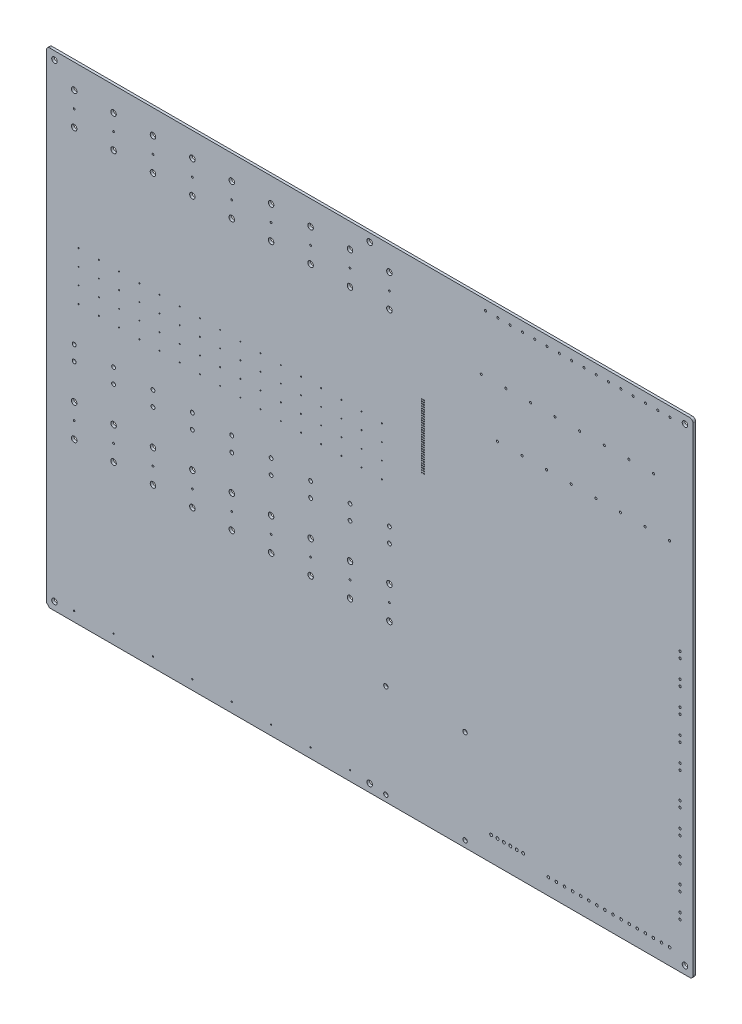
SolidWorks part; units mm, degrees
ref_plane "Front Plane" through (0, 0, 0) normal (0, 0, 1) x (1, 0, 0)
ref_plane "Top Plane" through (0, 0, 0) normal (0, 1, 0) x (1, 0, 0)
ref_plane "Right Plane" through (0, 0, 0) normal (1, 0, 0) x (0, 0, -1)
sketch "Sketch2" plane through (0, 0, 0) normal (0, 0, 1) x (1, 0, 0)
  line L1 (30, 30) -> (430, 30)
  line L2 (30, 30) -> (30, 330)
  line L3 (30, 330) -> (430, 330)
  line L4 (430, 30) -> (430, 330)
  dimension "D1" = 400
  dimension "D2" = 300
  dimension "D3" = 30
  dimension "D4" = 30
extrude "Boss-Extrude2" add sketch "Sketch2" along normal blind 1.6
fillet "Fillet1" radius 2 3 edges at (430, 30, 0.8) (430, 330, 0.8) (30, 330, 0.8)
chamfer "Chamfer1" distance 2 angle 45 1 edges at (30, 30, 0.8)
hole_wizard "6 x Ø3.4 Board Fixture " positions "Sketch3" profile "Sketch4" hole size "Ø3.4" standard "ISO"
sketch "Sketch3" plane through (0, 0, 1.6) normal (0, 0, 1) x (1, 0, 0)
  point P0 (35, 35)
  point P2 (230, 35)
  point P4 (425, 35)
  point P6 (425, 325)
  point P8 (230, 325)
  point P10 (35, 325)
  dimension "D1" = 35
  dimension "D2" = 230
  dimension "D3" = 425
  dimension "D4" = 35
  dimension "D5" = 325
sketch "Sketch4" plane through (35, 35, 1.6) normal (1, 0, 0) x (0, -1, 0)
  line L0 (0, 0) -> (0, 2.8215)
  line L1 (0, 2.8215) -> (1.7, 1.8)
  line L2 (1.7, 1.8) -> (1.7, 0)
  line L5 (1.7, 0) -> (0, 0)
  line L10 (0, 2.8215) -> (-1.7, 1.8) construction
  line L11 (0, -6.35) -> (0, 107.95) construction
  dimension "Hole Dia." = 3.4
  dimension "Hole Depth" = 1.8
  dimension "Drill Angle" = 118
sketch "Sketch9" plane through (0, 0, 1.6) normal (0, 0, 1) x (1, 0, 0)
  line L0 (47.188, 330) -> (47.188, 30) construction
  line L1 (428, 330) -> (32, 330) construction
  line L2 (32, 30) -> (428, 30) construction
  line L3 (71.563, 330) -> (71.563, 30) construction
  line L4 (95.938, 330) -> (95.938, 30) construction
  line L5 (120.313, 330) -> (120.313, 30) construction
  line L6 (144.688, 330) -> (144.688, 30) construction
  line L7 (169, 330) -> (169, 30) construction
  line L8 (193.446, 330) -> (193.446, 30) construction
  line L9 (217.812, 330) -> (217.812, 30) construction
  line L10 (242.188, 330) -> (242.188, 30) construction
  dimension "D1" = 47.188
  dimension "D2" = 71.563
  dimension "D3" = 95.938
  dimension "D4" = 120.313
  dimension "D5" = 144.688
  dimension "D6" = 169
  dimension "D7" = 193.446
  dimension "D8" = 217.812
  dimension "D9" = 242.188
hole_wizard "Ø3.4 (3.4) Diameter Hole3" positions "Sketch10" profile "Sketch11" hole size "Ø3.4" standard "ISO"
sketch "Sketch10" plane through (0, 0, 1.6) normal (0, 0, 1) x (1, 0, 0)
  line L0 (47.188, 330) -> (47.188, 30) construction
  line L1 (71.563, 330) -> (71.563, 30) construction
  line L2 (95.938, 330) -> (95.938, 30) construction
  line L3 (120.313, 330) -> (120.313, 30) construction
  line L4 (169, 330) -> (169, 30) construction
  line L5 (193.446, 330) -> (193.446, 30) construction
  line L6 (217.812, 330) -> (217.812, 30) construction
  line L7 (242.188, 330) -> (242.188, 30) construction
  line L8 (144.688, 330) -> (144.688, 30) construction
  point P0 (47.188, 314.956)
  point P2 (71.563, 314.956)
  point P4 (95.938, 314.956)
  point P6 (120.313, 314.956)
  point P8 (144.688, 314.956)
  point P10 (169, 314.956)
  point P12 (193.446, 314.956)
  point P14 (217.812, 314.956)
  point P16 (242.188, 314.956)
  point P18 (47.188, 294.956)
  point P20 (71.563, 294.956)
  point P22 (95.938, 294.956)
  point P24 (120.313, 294.956)
  point P26 (144.688, 294.956)
  point P28 (169, 294.956)
  point P30 (193.446, 294.956)
  point P32 (217.812, 294.956)
  point P34 (242.188, 294.956)
  point P36 (47.188, 147.956)
  point P38 (71.563, 147.956)
  point P40 (95.938, 147.956)
  point P42 (120.313, 147.956)
  point P44 (144.688, 147.956)
  point P46 (169, 147.956)
  point P48 (193.446, 147.956)
  point P50 (217.812, 147.956)
  point P52 (242.188, 147.956)
  point P54 (242.188, 127.956)
  point P56 (217.812, 127.956)
  point P58 (193.446, 127.956)
  point P60 (169, 127.956)
  point P62 (144.688, 127.956)
  point P64 (120.313, 127.956)
  point P66 (95.938, 127.956)
  point P68 (71.563, 127.956)
  point P70 (47.188, 127.956)
  dimension "D1" = 20
  dimension "D2" = 20
  dimension "D3" = 127.956
  dimension "D4" = 294.956
sketch "Sketch11" plane through (47.188, 314.956, 1.6) normal (1, 0, 0) x (0, -1, 0)
  line L0 (0, 0) -> (0, 2.8215)
  line L1 (0, 2.8215) -> (1.7, 1.8)
  line L2 (1.7, 1.8) -> (1.7, 0)
  line L5 (1.7, 0) -> (0, 0)
  line L10 (0, 2.8215) -> (-1.7, 1.8) construction
  line L11 (0, -6.35) -> (0, 107.95) construction
  dimension "Hole Dia." = 3.4
  dimension "Hole Depth" = 1.8
  dimension "Drill Angle" = 118
hole_wizard "Ø1.1 (1.1) Diameter Hole2" positions "Sketch12" profile "Sketch13" hole size "Ø1.1" standard "ISO"
sketch "Sketch12" plane through (0, 0, 1.6) normal (0, 0, 1) x (1, 0, 0)
  line L0 (47.188, 330) -> (47.188, 30) construction
  line L1 (71.563, 330) -> (71.563, 30) construction
  line L2 (95.938, 330) -> (95.938, 30) construction
  line L3 (120.313, 330) -> (120.313, 30) construction
  line L4 (144.688, 330) -> (144.688, 30) construction
  line L5 (169, 330) -> (169, 30) construction
  line L6 (193.446, 330) -> (193.446, 30) construction
  line L7 (217.812, 330) -> (217.812, 30) construction
  line L8 (242.188, 330) -> (242.188, 30) construction
  circle A0 centre (47.188, 314.956) radius 1.7 construction
  circle A1 centre (47.188, 127.956) radius 1.7 construction
  point P0 (47.188, 304.956)
  point P2 (71.563, 304.956)
  point P4 (95.938, 304.956)
  point P6 (120.313, 304.956)
  point P8 (144.688, 304.956)
  point P10 (169, 304.956)
  point P12 (193.446, 304.956)
  point P14 (217.812, 304.956)
  point P16 (242.188, 304.956)
  point P18 (47.188, 137.956)
  point P20 (71.563, 137.956)
  point P22 (95.938, 137.956)
  point P24 (120.313, 137.956)
  point P26 (144.688, 137.956)
  point P28 (169, 137.956)
  point P30 (193.446, 137.956)
  point P32 (217.812, 137.956)
  point P34 (242.188, 137.956)
  dimension "D1" = 10
  dimension "D2" = 10
sketch "Sketch13" plane through (47.188, 304.956, 1.6) normal (1, 0, 0) x (0, -1, 0)
  line L0 (0, 0) -> (0, 2.1305)
  line L1 (0, 2.1305) -> (0.55, 1.8)
  line L2 (0.55, 1.8) -> (0.55, 0)
  line L5 (0.55, 0) -> (0, 0)
  line L10 (0, 2.1305) -> (-0.55, 1.8) construction
  line L11 (0, -6.35) -> (0, 107.95) construction
  dimension "Hole Dia." = 1.1
  dimension "Hole Depth" = 1.8
  dimension "Drill Angle" = 118
hole_wizard "Ø2.35 (2.35) Diameter Hole1" positions "Sketch16" profile "Sketch17" hole size "Ø2.35" standard "ISO"
sketch "Sketch16" plane through (0, 0, 1.6) normal (0, 0, 1) x (1, 0, 0)
  line L0 (47.188, 330) -> (47.188, 30) construction
  line L1 (71.563, 330) -> (71.563, 30) construction
  line L2 (95.938, 330) -> (95.938, 30) construction
  line L3 (120.313, 330) -> (120.313, 30) construction
  line L4 (144.688, 330) -> (144.688, 30) construction
  line L5 (169, 330) -> (169, 30) construction
  line L6 (193.446, 330) -> (193.446, 30) construction
  line L7 (217.812, 330) -> (217.812, 30) construction
  line L8 (242.188, 330) -> (242.188, 30) construction
  point P0 (47.188, 178.778)
  point P2 (71.563, 178.778)
  point P4 (95.938, 178.778)
  point P6 (120.313, 178.778)
  point P8 (144.688, 178.778)
  point P10 (169, 178.778)
  point P12 (193.446, 178.778)
  point P14 (217.812, 178.778)
  point P16 (242.188, 178.778)
  point P48 (47.188, 169.628)
  point P50 (71.563, 169.628)
  point P52 (95.938, 169.628)
  point P54 (120.313, 169.628)
  point P56 (144.688, 169.628)
  point P58 (169, 169.628)
  point P60 (193.446, 169.628)
  point P62 (217.812, 169.628)
  point P64 (242.188, 169.628)
  dimension "D1" = 178.778
  dimension "D2" = 9.15
sketch "Sketch17" plane through (47.188, 178.778, 1.6) normal (1, 0, 0) x (0, -1, 0)
  line L0 (0, 0) -> (0, 2.506)
  line L1 (0, 2.506) -> (1.175, 1.8)
  line L2 (1.175, 1.8) -> (1.175, 0)
  line L5 (1.175, 0) -> (0, 0)
  line L10 (0, 2.506) -> (-1.175, 1.8) construction
  line L11 (0, -6.35) -> (0, 107.95) construction
  dimension "Hole Dia." = 2.35
  dimension "Hole Depth" = 1.8
  dimension "Drill Angle" = 118
hole_wizard "Ø0.8 (0.8) Diameter Hole1" positions "Sketch18" profile "Sketch19" hole size "Ø0.8" standard "ISO"
sketch "Sketch18" plane through (0, 0, 1.6) normal (0, 0, 1) x (1, 0, 0)
  line L0 (47.188, 330) -> (47.188, 30) construction
  line L1 (71.563, 330) -> (71.563, 30) construction
  line L2 (95.938, 330) -> (95.938, 30) construction
  line L3 (120.313, 330) -> (120.313, 30) construction
  line L4 (144.688, 330) -> (144.688, 30) construction
  line L5 (169, 330) -> (169, 30) construction
  line L6 (193.446, 330) -> (193.446, 30) construction
  line L7 (217.812, 330) -> (217.812, 30) construction
  point P0 (47.188, 36)
  point P2 (71.563, 36)
  point P4 (95.938, 36)
  point P6 (120.313, 36)
  point P8 (144.688, 36)
  point P10 (169, 36)
  point P12 (193.446, 36)
  point P14 (217.812, 36)
  dimension "D1" = 36
sketch "Sketch19" plane through (47.188, 36, 1.6) normal (1, 0, 0) x (0, -1, 0)
  line L0 (0, 0) -> (0, 2.0403)
  line L1 (0, 2.0403) -> (0.4, 1.8)
  line L2 (0.4, 1.8) -> (0.4, 0)
  line L5 (0.4, 0) -> (0, 0)
  line L10 (0, 2.0403) -> (-0.4, 1.8) construction
  line L11 (0, -6.35) -> (0, 107.95) construction
  dimension "Hole Dia." = 0.8
  dimension "Hole Depth" = 1.8
  dimension "Drill Angle" = 118
hole_wizard "Ø2.7 (2.7) Diameter Hole1" positions "Sketch20" profile "Sketch21" hole size "Ø2.7" standard "ISO"
sketch "Sketch20" plane through (0, 0, 1.6) normal (0, 0, 1) x (1, 0, 0)
  point P0 (239.994, 34)
  point P2 (239.994, 92)
  point P4 (288.994, 92)
  point P6 (288.994, 34)
  dimension "D1" = 239.994
  dimension "D2" = 288.994
  dimension "D3" = 34
  dimension "D4" = 92
sketch "Sketch21" plane through (239.994, 34, 1.6) normal (1, 0, 0) x (0, -1, 0)
  line L0 (0, 0) -> (0, 2.6112)
  line L1 (0, 2.6112) -> (1.35, 1.8)
  line L2 (1.35, 1.8) -> (1.35, 0)
  line L5 (1.35, 0) -> (0, 0)
  line L10 (0, 2.6112) -> (-1.35, 1.8) construction
  line L11 (0, -6.35) -> (0, 107.95) construction
  dimension "Hole Dia." = 2.7
  dimension "Hole Depth" = 1.8
  dimension "Drill Angle" = 118
hole_wizard "Ø1.8 (1.8) Diameter Hole1" positions "Sketch22" profile "Sketch23" hole size "Ø1.8" standard "ISO"
sketch "Sketch22" plane through (0, 0, 1.6) normal (0, 0, 1) x (1, 0, 0)
  point P0 (305.1, 45)
  point P2 (309.06, 45)
  point P4 (313.02, 45)
  point P6 (316.98, 45)
  point P8 (320.94, 45)
  point P10 (324.9, 45)
  dimension "D1" = 3.96
  dimension "D2" = 3.96
  dimension "D3" = 3.96
  dimension "D4" = 3.96
  dimension "D5" = 3.96
  dimension "D6" = 305.1
  dimension "D7" = 45
sketch "Sketch23" plane through (305.1, 45, 1.6) normal (1, 0, 0) x (0, -1, 0)
  line L0 (0, 0) -> (0, 2.3408)
  line L1 (0, 2.3408) -> (0.9, 1.8)
  line L2 (0.9, 1.8) -> (0.9, 0)
  line L5 (0.9, 0) -> (0, 0)
  line L10 (0, 2.3408) -> (-0.9, 1.8) construction
  line L11 (0, -6.35) -> (0, 107.95) construction
  dimension "Hole Dia." = 1.8
  dimension "Hole Depth" = 1.8
  dimension "Drill Angle" = 118
hole_wizard "Ø1.6 (1.6) Diameter Hole1" positions "Sketch24" profile "Sketch25" hole size "Ø1.6" standard "ISO"
sketch "Sketch24" plane through (0, 0, 1.6) normal (0, 0, 1) x (1, 0, 0)
  point P0 (340.5, 40)
  point P2 (345.5, 40)
  point P4 (350.5, 40)
  point P6 (355.5, 40)
  point P8 (360.5, 40)
  point P10 (365.5, 40)
  point P12 (370.5, 40)
  point P14 (375.5, 40)
  point P16 (380.5, 40)
  point P18 (385.5, 40)
  point P20 (390.5, 40)
  point P22 (395.5, 40)
  point P24 (400.5, 40)
  point P26 (405.5, 40)
  point P28 (410.5, 40)
  point P30 (415.5, 40)
  dimension "D1" = 5
  dimension "D2" = 5
  dimension "D3" = 5
  dimension "D4" = 5
  dimension "D5" = 5
  dimension "D6" = 5
  dimension "D7" = 5
  dimension "D8" = 5
  dimension "D9" = 5
  dimension "D10" = 5
  dimension "D11" = 5
  dimension "D12" = 5
  dimension "D13" = 5
  dimension "D14" = 5
  dimension "D15" = 5
  dimension "D16" = 340.5
  dimension "D17" = 40
sketch "Sketch25" plane through (340.5, 40, 1.6) normal (1, 0, 0) x (0, -1, 0)
  line L0 (0, 0) -> (0, 2.2807)
  line L1 (0, 2.2807) -> (0.8, 1.8)
  line L2 (0.8, 1.8) -> (0.8, 0)
  line L5 (0.8, 0) -> (0, 0)
  line L10 (0, 2.2807) -> (-0.8, 1.8) construction
  line L11 (0, -6.35) -> (0, 107.95) construction
  dimension "Hole Dia." = 1.6
  dimension "Hole Depth" = 1.8
  dimension "Drill Angle" = 118
hole_wizard "Ø1.4 (1.4) Diameter Hole1" positions "Sketch26" profile "Sketch27" hole size "Ø1.4" standard "ISO"
sketch "Sketch26" plane through (0, 0, 1.6) normal (0, 0, 1) x (1, 0, 0)
  point P0 (422, 58.095)
  point P2 (422, 61.895)
  point P4 (422, 73.085)
  point P6 (422, 76.885)
  point P8 (422, 88.075)
  point P10 (422, 91.875)
  point P12 (422, 103.065)
  point P14 (422, 106.865)
  point P16 (422, 118.055)
  point P18 (422, 121.855)
  point P20 (422, 138.045)
  point P22 (422, 141.845)
  point P24 (422, 153.035)
  point P26 (422, 156.835)
  point P28 (422, 168.025)
  point P30 (422, 171.825)
  point P32 (422, 183.015)
  point P34 (422, 186.815)
  point P36 (422, 198.005)
  point P38 (422, 201.805)
  dimension "D1" = 3.8
  dimension "D2" = 11.19
  dimension "D3" = 3.8
  dimension "D4" = 11.19
  dimension "D5" = 3.8
  dimension "D6" = 11.19
  dimension "D7" = 3.8
  dimension "D8" = 11.19
  dimension "D9" = 3.8
  dimension "D10" = 16.19
  dimension "D11" = 3.8
  dimension "D12" = 11.19
  dimension "D13" = 3.8
  dimension "D14" = 11.19
  dimension "D15" = 3.8
  dimension "D16" = 11.19
  dimension "D17" = 3.8
  dimension "D18" = 11.19
  dimension "D19" = 3.8
  dimension "D20" = 422
  dimension "D21" = 58.095
sketch "Sketch27" plane through (422, 58.095, 1.6) normal (1, 0, 0) x (0, -1, 0)
  line L0 (0, 0) -> (0, 2.2206)
  line L1 (0, 2.2206) -> (0.7, 1.8)
  line L2 (0.7, 1.8) -> (0.7, 0)
  line L5 (0.7, 0) -> (0, 0)
  line L10 (0, 2.2206) -> (-0.7, 1.8) construction
  line L11 (0, -6.35) -> (0, 107.95) construction
  dimension "Hole Dia." = 1.4
  dimension "Hole Depth" = 1.8
  dimension "Drill Angle" = 118
hole_wizard "Ø1.3 (1.3) Diameter Hole1" positions "Sketch28" profile "Sketch29" hole size "Ø1.3" standard "ISO"
sketch "Sketch28" plane through (0, 0, 1.6) normal (0, 0, 1) x (1, 0, 0)
  point P0 (301.655, 324)
  dimension "D1" = 301.655
  dimension "D2" = 324
sketch "Sketch29" plane through (301.655, 324, 1.6) normal (1, 0, 0) x (0, -1, 0)
  line L0 (0, 0) -> (0, 2.1906)
  line L1 (0, 2.1906) -> (0.65, 1.8)
  line L2 (0.65, 1.8) -> (0.65, 0)
  line L5 (0.65, 0) -> (0, 0)
  line L10 (0, 2.1906) -> (-0.65, 1.8) construction
  line L11 (0, -6.35) -> (0, 107.95) construction
  dimension "Hole Dia." = 1.3
  dimension "Hole Depth" = 1.8
  dimension "Drill Angle" = 118
pattern_linear "LPattern1" count 16 spacing 7.61 along (1, 0, 0) of "Ø1.3 (1.3) Diameter Hole1"
hole_wizard "Ø1.3 (1.3) Diameter Hole2" positions "Sketch30" profile "Sketch31" hole size "Ø1.3" standard "ISO"
sketch "Sketch30" plane through (0, 0, 1.6) normal (0, 0, 1) x (1, 0, 0)
  point P0 (309, 257.7)
  point P2 (324.22, 257.7)
  point P4 (339.44, 257.7)
  point P6 (354.66, 257.7)
  point P8 (369.88, 257.7)
  point P10 (385.1, 257.7)
  point P12 (400.32, 257.7)
  point P14 (415.54, 257.7)
  point P16 (299, 288.7)
  point P18 (314.22, 288.7)
  point P20 (329.44, 288.7)
  point P22 (344.66, 288.7)
  point P24 (359.88, 288.7)
  point P26 (375.1, 288.7)
  point P28 (390.32, 288.7)
  point P30 (405.54, 288.7)
  dimension "D1" = 309
  dimension "D2" = 257.7
  dimension "D3" = 15.22
  dimension "D4" = 15.22
  dimension "D5" = 15.22
  dimension "D6" = 15.22
  dimension "D7" = 15.22
  dimension "D8" = 15.22
  dimension "D9" = 15.22
  dimension "D10" = 10
  dimension "D11" = 31
  dimension "D12" = 15.22
  dimension "D13" = 15.22
  dimension "D14" = 15.22
  dimension "D15" = 15.22
  dimension "D16" = 15.22
  dimension "D17" = 15.22
  dimension "D18" = 15.22
sketch "Sketch31" plane through (309, 257.7, 1.6) normal (1, 0, 0) x (0, -1, 0)
  line L0 (0, 0) -> (0, 2.1906)
  line L1 (0, 2.1906) -> (0.65, 1.8)
  line L2 (0.65, 1.8) -> (0.65, 0)
  line L5 (0.65, 0) -> (0, 0)
  line L10 (0, 2.1906) -> (-0.65, 1.8) construction
  line L11 (0, -6.35) -> (0, 107.95) construction
  dimension "Hole Dia." = 1.3
  dimension "Hole Depth" = 1.8
  dimension "Drill Angle" = 118
hole_wizard "Ø0.65 (0.65) Diameter Hole1" positions "Sketch32" profile "Sketch33" hole size "Ø0.65" standard "ISO"
sketch "Sketch32" plane through (0, 0, 1.6) normal (0, 0, 1) x (1, 0, 0)
  point P0 (50, 201.698)
  dimension "D1" = 50
  dimension "D2" = 201.698
sketch "Sketch33" plane through (50, 201.698, 1.6) normal (1, 0, 0) x (0, -1, 0)
  line L0 (0, 0) -> (0, 1.9953)
  line L1 (0, 1.9953) -> (0.325, 1.8)
  line L2 (0.325, 1.8) -> (0.325, 0)
  line L5 (0.325, 0) -> (0, 0)
  line L10 (0, 1.9953) -> (-0.325, 1.8) construction
  line L11 (0, -6.35) -> (0, 107.95) construction
  dimension "Hole Dia." = 0.65
  dimension "Hole Depth" = 1.8
  dimension "Drill Angle" = 118
pattern_linear "LPattern2" count 16 spacing 12.5 along (1, 0, 0) count 4 spacing 10 along (0, 1, 0) of "Ø0.65 (0.65) Diameter Hole1"
hole_wizard "Ø0.65 (0.65) Diameter Hole2" positions "Sketch34" profile "Sketch35" hole size "Ø0.65" standard "DIN" end condition through all
sketch "Sketch34" plane through (0, 0, 1.6) normal (0, 0, 1) x (1, 0, 0)
  point P0 (262.268, 257.085)
  dimension "D1" = 262.268
  dimension "D2" = 257.085
sketch "Sketch35" plane through (262.268, 257.085, 1.6) normal (1, 0, 0) x (0, -1, 0)
  line L0 (0, 0) -> (0, 1.6)
  line L1 (0, 1.6) -> (0.325, 1.6)
  line L2 (0.325, 1.6) -> (0.325, 0)
  line L5 (0.325, 0) -> (0, 0)
  line L11 (0, -6.35) -> (0, 107.95) construction
  dimension "Thru Hole Dia." = 0.65
  dimension "Thru Hole Depth" = 1.6
pattern_linear "LPattern3" count 32 spacing 1.27 along (0, -1, 0) count 2 spacing 1.27 along (1, 0, 0) of "Ø0.65 (0.65) Diameter Hole2"
